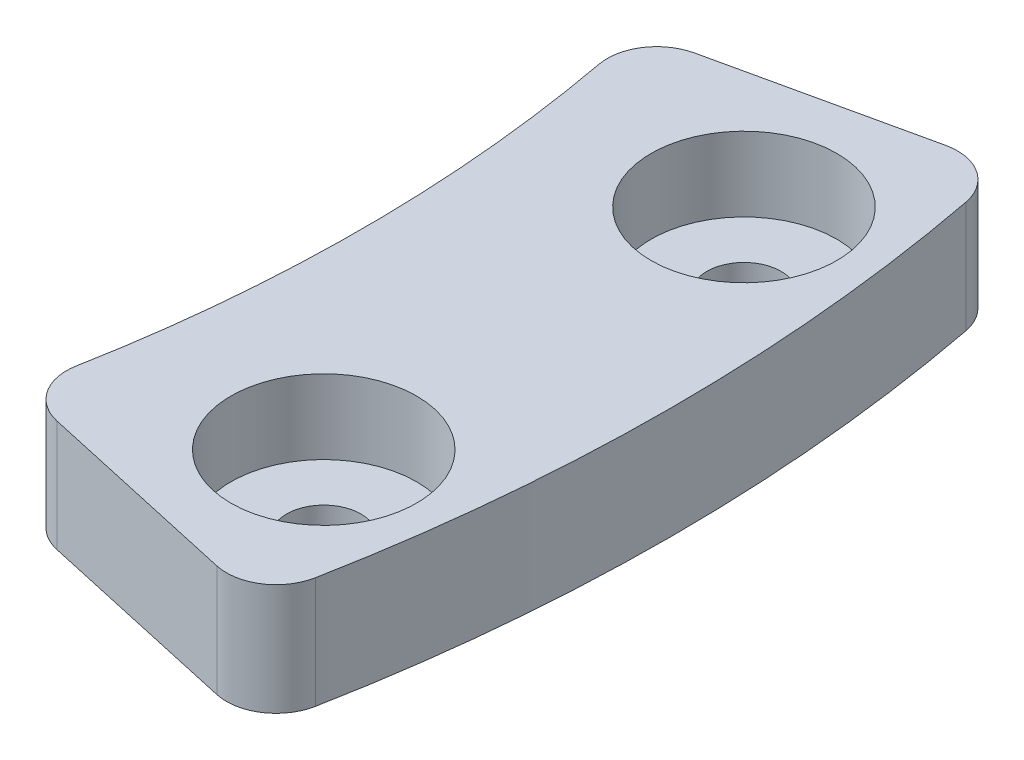
SolidWorks part; units mm, degrees
material "5052-H34"
ref_plane "正面" through (0, 0, 0) normal (0, 0, 1) x (1, 0, 0)
ref_plane "平面" through (0, 0, 0) normal (0, 1, 0) x (1, 0, 0)
ref_plane "右側面" through (0, 0, 0) normal (1, 0, 0) x (0, 0, -1)
sketch "ｽｹｯﾁ1" plane through (0, 0, 0) normal (0, 1, 0) x (1, 0, 0)
  line L0 (57.5, 0) -> (70, 0) construction
  line L1 (57.0081, 7.5053) -> (64.4439, 8.4842) construction
  line L2 (56.137, 12.4453) -> (68.3407, 15.1508)
  line L3 (56.137, -12.4453) -> (68.3407, -15.1508)
  line L4 (0, 0) -> (56.137, 12.4453) construction
  line L5 (0, 0) -> (57.0081, 7.5053) construction
  line L6 (0, 0) -> (57.5, 0) construction
  line L7 (0, 0) -> (56.137, -12.4453) construction
  arc A0 (68.3407, -15.1508) -> (68.3407, 15.1508) centre (0, 0) ccw
  arc A1 (56.137, -12.4453) -> (56.137, 12.4453) centre (0, 0) ccw
  circle A2 centre (64.4439, 8.4842) radius 1.5
  arc A3 (63.4592, -14.0686) -> (63.4592, 14.0686) centre (0, 0) ccw construction
  circle A4 centre (64.4439, -8.4842) radius 1.5
  arc A5 (63.4592, 14.0686) -> (63.4592, -14.0686) centre (0, 0) ccw construction
  arc A6 (68.3407, 15.1508) -> (68.3407, -15.1508) centre (0, 0) ccw construction
  arc A7 (56.137, 12.4453) -> (56.137, -12.4453) centre (0, 0) ccw construction
  dimension "D1" = 140
  dimension "D2" = 115
  dimension "D3" = 130
  dimension "D4" = 3
  dimension "D5" = 7.5
  dimension "D6" = 12.5
extrude "ﾎﾞｽ - 押し出し1" add sketch "ｽｹｯﾁ1" along normal blind 4.5
fillet "ﾌｨﾚｯﾄ1" radius 2 4 edges at (68.3407, 2.25, 15.1508) (56.137, 2.25, 12.4453) (68.3407, 2.25, -15.1508) (56.137, 2.25, -12.4453)
sketch "ｽｹｯﾁ2" plane through (0, 4.5, 0) normal (0, 1, 0) x (1, 0, 0)
  circle A0 centre (64.4439, 8.4842) radius 3.75
  circle A1 centre (64.4439, -8.4842) radius 3.75
  dimension "D1" = 7.5
extrude "ｶｯﾄ - 押し出し1" cut sketch "ｽｹｯﾁ2" against normal blind 3
